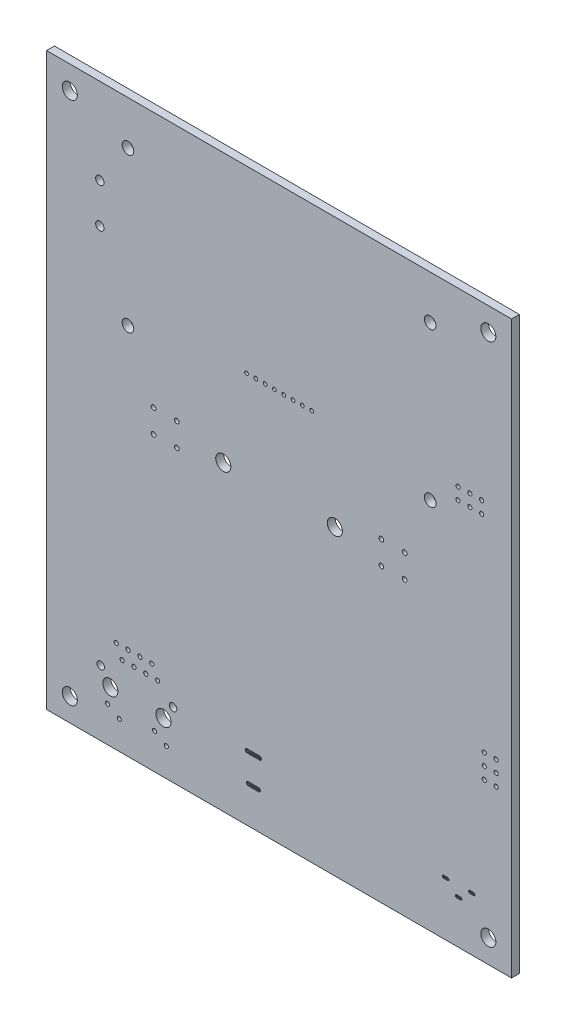
SolidWorks part; units mm, degrees
ref_plane "Front Plane" through (0, 0, 0) normal (0, 0, 1) x (1, 0, 0)
ref_plane "Top Plane" through (0, 0, 0) normal (0, 1, 0) x (1, 0, 0)
ref_plane "Right Plane" through (0, 0, 0) normal (1, 0, 0) x (0, 0, -1)
sketch "Sketch1" plane through (0, 0, 0) normal (0, 0, -1) x (-1, 0, 0)
  line L0 (7.946, 11.777) -> (8.045, 11.844)
  line L1 (8.045, 11.844) -> (8.162, 11.867)
  line L2 (8.162, 11.867) -> (8.234, 11.853)
  line L3 (8.234, 11.853) -> (8.306, 11.867)
  line L4 (8.306, 11.867) -> (8.382, 11.852)
  line L5 (8.382, 11.852) -> (8.458, 11.867)
  line L6 (8.458, 11.867) -> (8.509, 11.857)
  line L7 (8.509, 11.857) -> (8.56, 11.867)
  line L8 (8.56, 11.867) -> (8.636, 11.852)
  line L9 (8.636, 11.852) -> (8.712, 11.867)
  line L10 (8.712, 11.867) -> (8.776, 11.854)
  line L11 (8.776, 11.854) -> (8.839, 11.867)
  line L12 (8.839, 11.867) -> (8.901, 11.855)
  line L13 (8.901, 11.855) -> (8.962, 11.867)
  line L14 (8.962, 11.867) -> (9.079, 11.844)
  line L15 (9.079, 11.844) -> (9.179, 11.777)
  line L16 (9.179, 11.777) -> (9.245, 11.678)
  line L17 (9.245, 11.678) -> (9.268, 11.561)
  line L18 (9.268, 11.561) -> (9.245, 11.444)
  line L19 (9.245, 11.444) -> (9.179, 11.345)
  line L20 (9.179, 11.345) -> (9.079, 11.279)
  line L21 (9.079, 11.279) -> (8.962, 11.255)
  line L22 (8.962, 11.255) -> (8.901, 11.268)
  line L23 (8.901, 11.268) -> (8.839, 11.255)
  line L24 (8.839, 11.255) -> (8.776, 11.268)
  line L25 (8.776, 11.268) -> (8.712, 11.255)
  line L26 (8.712, 11.255) -> (8.636, 11.27)
  line L27 (8.636, 11.27) -> (8.56, 11.255)
  line L28 (8.56, 11.255) -> (8.509, 11.265)
  line L29 (8.509, 11.265) -> (8.458, 11.255)
  line L30 (8.458, 11.255) -> (8.382, 11.27)
  line L31 (8.382, 11.27) -> (8.306, 11.255)
  line L32 (8.306, 11.255) -> (8.234, 11.27)
  line L33 (8.234, 11.27) -> (8.162, 11.255)
  line L34 (8.162, 11.255) -> (8.045, 11.279)
  line L35 (8.045, 11.279) -> (7.946, 11.345)
  line L36 (7.946, 11.345) -> (7.88, 11.444)
  line L37 (7.88, 11.444) -> (7.857, 11.561)
  line L38 (7.857, 11.561) -> (7.88, 11.678)
  line L39 (7.88, 11.678) -> (7.946, 11.777)
  line L40 (13.574, 11.777) -> (13.673, 11.844)
  line L41 (13.673, 11.844) -> (13.79, 11.867)
  line L42 (13.79, 11.867) -> (13.862, 11.853)
  line L43 (13.862, 11.853) -> (13.933, 11.867)
  line L44 (13.933, 11.867) -> (14.01, 11.852)
  line L45 (14.01, 11.852) -> (14.086, 11.867)
  line L46 (14.086, 11.867) -> (14.137, 11.857)
  line L47 (14.137, 11.857) -> (14.187, 11.867)
  line L48 (14.187, 11.867) -> (14.264, 11.852)
  line L49 (14.264, 11.852) -> (14.34, 11.867)
  line L50 (14.34, 11.867) -> (14.403, 11.854)
  line L51 (14.403, 11.854) -> (14.467, 11.867)
  line L52 (14.467, 11.867) -> (14.528, 11.855)
  line L53 (14.528, 11.855) -> (14.59, 11.867)
  line L54 (14.59, 11.867) -> (14.707, 11.844)
  line L55 (14.707, 11.844) -> (14.806, 11.777)
  line L56 (14.806, 11.777) -> (14.872, 11.678)
  line L57 (14.872, 11.678) -> (14.896, 11.561)
  line L58 (14.896, 11.561) -> (14.872, 11.444)
  line L59 (14.872, 11.444) -> (14.806, 11.345)
  line L60 (14.806, 11.345) -> (14.707, 11.279)
  line L61 (14.707, 11.279) -> (14.59, 11.255)
  line L62 (14.59, 11.255) -> (14.528, 11.268)
  line L63 (14.528, 11.268) -> (14.467, 11.255)
  line L64 (14.467, 11.255) -> (14.403, 11.268)
  line L65 (14.403, 11.268) -> (14.34, 11.255)
  line L66 (14.34, 11.255) -> (14.264, 11.27)
  line L67 (14.264, 11.27) -> (14.187, 11.255)
  line L68 (14.187, 11.255) -> (14.137, 11.265)
  line L69 (14.137, 11.265) -> (14.086, 11.255)
  line L70 (14.086, 11.255) -> (14.01, 11.27)
  line L71 (14.01, 11.27) -> (13.933, 11.255)
  line L72 (13.933, 11.255) -> (13.862, 11.27)
  line L73 (13.862, 11.27) -> (13.79, 11.255)
  line L74 (13.79, 11.255) -> (13.673, 11.279)
  line L75 (13.673, 11.279) -> (13.574, 11.345)
  line L76 (13.574, 11.345) -> (13.507, 11.444)
  line L77 (13.507, 11.444) -> (13.484, 11.561)
  line L78 (13.484, 11.561) -> (13.507, 11.678)
  line L79 (13.507, 11.678) -> (13.574, 11.777)
  line L80 (11.286, 9.636) -> (11.329, 9.627)
  line L81 (11.329, 9.627) -> (11.387, 9.639)
  line L82 (11.387, 9.639) -> (11.472, 9.622)
  line L83 (11.472, 9.622) -> (11.54, 9.636)
  line L84 (11.54, 9.636) -> (11.603, 9.623)
  line L85 (11.603, 9.623) -> (11.667, 9.636)
  line L86 (11.667, 9.636) -> (11.728, 9.623)
  line L87 (11.728, 9.623) -> (11.79, 9.636)
  line L88 (11.79, 9.636) -> (11.907, 9.612)
  line L89 (11.907, 9.612) -> (12.006, 9.546)
  line L90 (12.006, 9.546) -> (12.072, 9.447)
  line L91 (12.072, 9.447) -> (12.096, 9.33)
  line L92 (12.096, 9.33) -> (12.072, 9.213)
  line L93 (12.072, 9.213) -> (12.006, 9.114)
  line L94 (12.006, 9.114) -> (11.907, 9.047)
  line L95 (11.907, 9.047) -> (11.79, 9.024)
  line L96 (11.79, 9.024) -> (11.728, 9.036)
  line L97 (11.728, 9.036) -> (11.667, 9.024)
  line L98 (11.667, 9.024) -> (11.603, 9.037)
  line L99 (11.603, 9.037) -> (11.54, 9.024)
  line L100 (11.54, 9.024) -> (11.456, 9.041)
  line L101 (11.456, 9.041) -> (11.387, 9.027)
  line L102 (11.387, 9.027) -> (11.345, 9.036)
  line L103 (11.345, 9.036) -> (11.286, 9.024)
  line L104 (11.286, 9.024) -> (11.21, 9.039)
  line L105 (11.21, 9.039) -> (11.133, 9.024)
  line L106 (11.133, 9.024) -> (11.062, 9.038)
  line L107 (11.062, 9.038) -> (10.99, 9.024)
  line L108 (10.99, 9.024) -> (10.873, 9.047)
  line L109 (10.873, 9.047) -> (10.774, 9.114)
  line L110 (10.774, 9.114) -> (10.707, 9.213)
  line L111 (10.707, 9.213) -> (10.684, 9.33)
  line L112 (10.684, 9.33) -> (10.707, 9.447)
  line L113 (10.707, 9.447) -> (10.774, 9.546)
  line L114 (10.774, 9.546) -> (10.873, 9.612)
  line L115 (10.873, 9.612) -> (10.99, 9.636)
  line L116 (10.99, 9.636) -> (11.062, 9.621)
  line L117 (11.062, 9.621) -> (11.133, 9.636)
  line L118 (11.133, 9.636) -> (11.21, 9.621)
  line L119 (11.21, 9.621) -> (11.286, 9.636)
  line L120 (55.34, 14.234) -> (55.372, 14.255)
  line L121 (55.372, 14.255) -> (55.528, 14.286)
  line L122 (55.528, 14.286) -> (55.684, 14.255)
  line L123 (55.684, 14.255) -> (55.691, 14.25)
  line L124 (55.691, 14.25) -> (55.697, 14.255)
  line L125 (55.697, 14.255) -> (55.853, 14.286)
  line L126 (55.853, 14.286) -> (56.003, 14.256)
  line L127 (56.003, 14.256) -> (56.153, 14.286)
  line L128 (56.153, 14.286) -> (56.309, 14.255)
  line L129 (56.309, 14.255) -> (56.315, 14.25)
  line L130 (56.315, 14.25) -> (56.322, 14.255)
  line L131 (56.322, 14.255) -> (56.478, 14.286)
  line L132 (56.478, 14.286) -> (56.634, 14.255)
  line L133 (56.634, 14.255) -> (56.678, 14.225)
  line L134 (56.678, 14.225) -> (56.722, 14.255)
  line L135 (56.722, 14.255) -> (56.878, 14.286)
  line L136 (56.878, 14.286) -> (57.034, 14.255)
  line L137 (57.034, 14.255) -> (57.166, 14.166)
  line L138 (57.166, 14.166) -> (57.255, 14.034)
  line L139 (57.255, 14.034) -> (57.286, 13.878)
  line L140 (57.286, 13.878) -> (57.255, 13.722)
  line L141 (57.255, 13.722) -> (57.166, 13.59)
  line L142 (57.166, 13.59) -> (57.034, 13.501)
  line L143 (57.034, 13.501) -> (56.878, 13.47)
  line L144 (56.878, 13.47) -> (56.722, 13.501)
  line L145 (56.722, 13.501) -> (56.678, 13.531)
  line L146 (56.678, 13.531) -> (56.634, 13.501)
  line L147 (56.634, 13.501) -> (56.478, 13.47)
  line L148 (56.478, 13.47) -> (56.322, 13.501)
  line L149 (56.322, 13.501) -> (56.315, 13.506)
  line L150 (56.315, 13.506) -> (56.309, 13.501)
  line L151 (56.309, 13.501) -> (56.153, 13.47)
  line L152 (56.153, 13.47) -> (56.003, 13.5)
  line L153 (56.003, 13.5) -> (55.853, 13.47)
  line L154 (55.853, 13.47) -> (55.697, 13.501)
  line L155 (55.697, 13.501) -> (55.69, 13.506)
  line L156 (55.69, 13.506) -> (55.684, 13.501)
  line L157 (55.684, 13.501) -> (55.528, 13.47)
  line L158 (55.528, 13.47) -> (55.372, 13.501)
  line L159 (55.372, 13.501) -> (55.341, 13.522)
  line L160 (55.341, 13.522) -> (55.309, 13.501)
  line L161 (55.309, 13.501) -> (55.153, 13.47)
  line L162 (55.153, 13.47) -> (54.997, 13.501)
  line L163 (54.997, 13.501) -> (54.99, 13.506)
  line L164 (54.99, 13.506) -> (54.984, 13.501)
  line L165 (54.984, 13.501) -> (54.828, 13.47)
  line L166 (54.828, 13.47) -> (54.672, 13.501)
  line L167 (54.672, 13.501) -> (54.665, 13.506)
  line L168 (54.665, 13.506) -> (54.659, 13.501)
  line L169 (54.659, 13.501) -> (54.503, 13.47)
  line L170 (54.503, 13.47) -> (54.347, 13.501)
  line L171 (54.347, 13.501) -> (54.341, 13.506)
  line L172 (54.341, 13.506) -> (54.334, 13.501)
  line L173 (54.334, 13.501) -> (54.178, 13.47)
  line L174 (54.178, 13.47) -> (54.022, 13.501)
  line L175 (54.022, 13.501) -> (53.89, 13.59)
  line L176 (53.89, 13.59) -> (53.801, 13.722)
  line L177 (53.801, 13.722) -> (53.77, 13.878)
  line L178 (53.77, 13.878) -> (53.801, 14.034)
  line L179 (53.801, 14.034) -> (53.89, 14.166)
  line L180 (53.89, 14.166) -> (54.022, 14.255)
  line L181 (54.022, 14.255) -> (54.178, 14.286)
  line L182 (54.178, 14.286) -> (54.334, 14.255)
  line L183 (54.334, 14.255) -> (54.341, 14.25)
  line L184 (54.341, 14.25) -> (54.347, 14.255)
  line L185 (54.347, 14.255) -> (54.503, 14.286)
  line L186 (54.503, 14.286) -> (54.659, 14.255)
  line L187 (54.659, 14.255) -> (54.665, 14.25)
  line L188 (54.665, 14.25) -> (54.672, 14.255)
  line L189 (54.672, 14.255) -> (54.828, 14.286)
  line L190 (54.828, 14.286) -> (54.984, 14.255)
  line L191 (54.984, 14.255) -> (54.99, 14.25)
  line L192 (54.99, 14.25) -> (54.997, 14.255)
  line L193 (54.997, 14.255) -> (55.153, 14.286)
  line L194 (55.153, 14.286) -> (55.309, 14.255)
  line L195 (55.309, 14.255) -> (55.34, 14.234)
  line L196 (54.14, 8.166) -> (54.272, 8.255)
  line L197 (54.272, 8.255) -> (54.428, 8.286)
  line L198 (54.428, 8.286) -> (54.584, 8.255)
  line L199 (54.584, 8.255) -> (54.628, 8.225)
  line L200 (54.628, 8.225) -> (54.672, 8.255)
  line L201 (54.672, 8.255) -> (54.828, 8.286)
  line L202 (54.828, 8.286) -> (54.984, 8.255)
  line L203 (54.984, 8.255) -> (55.015, 8.234)
  line L204 (55.015, 8.234) -> (55.047, 8.255)
  line L205 (55.047, 8.255) -> (55.203, 8.286)
  line L206 (55.203, 8.286) -> (55.359, 8.255)
  line L207 (55.359, 8.255) -> (55.365, 8.25)
  line L208 (55.365, 8.25) -> (55.372, 8.255)
  line L209 (55.372, 8.255) -> (55.528, 8.286)
  line L210 (55.528, 8.286) -> (55.684, 8.255)
  line L211 (55.684, 8.255) -> (55.74, 8.217)
  line L212 (55.74, 8.217) -> (55.797, 8.255)
  line L213 (55.797, 8.255) -> (55.953, 8.286)
  line L214 (55.953, 8.286) -> (56.109, 8.255)
  line L215 (56.109, 8.255) -> (56.153, 8.225)
  line L216 (56.153, 8.225) -> (56.197, 8.255)
  line L217 (56.197, 8.255) -> (56.353, 8.286)
  line L218 (56.353, 8.286) -> (56.49, 8.258)
  line L219 (56.49, 8.258) -> (56.628, 8.286)
  line L220 (56.628, 8.286) -> (56.784, 8.255)
  line L221 (56.784, 8.255) -> (56.916, 8.166)
  line L222 (56.916, 8.166) -> (57.005, 8.034)
  line L223 (57.005, 8.034) -> (57.036, 7.878)
  line L224 (57.036, 7.878) -> (57.005, 7.722)
  line L225 (57.005, 7.722) -> (56.916, 7.59)
  line L226 (56.916, 7.59) -> (56.784, 7.501)
  line L227 (56.784, 7.501) -> (56.628, 7.47)
  line L228 (56.628, 7.47) -> (56.49, 7.498)
  line L229 (56.49, 7.498) -> (56.353, 7.47)
  line L230 (56.353, 7.47) -> (56.197, 7.501)
  line L231 (56.197, 7.501) -> (56.153, 7.531)
  line L232 (56.153, 7.531) -> (56.109, 7.501)
  line L233 (56.109, 7.501) -> (55.953, 7.47)
  line L234 (55.953, 7.47) -> (55.797, 7.501)
  line L235 (55.797, 7.501) -> (55.74, 7.539)
  line L236 (55.74, 7.539) -> (55.684, 7.501)
  line L237 (55.684, 7.501) -> (55.528, 7.47)
  line L238 (55.528, 7.47) -> (55.372, 7.501)
  line L239 (55.372, 7.501) -> (55.365, 7.506)
  line L240 (55.365, 7.506) -> (55.359, 7.501)
  line L241 (55.359, 7.501) -> (55.203, 7.47)
  line L242 (55.203, 7.47) -> (55.047, 7.501)
  line L243 (55.047, 7.501) -> (55.015, 7.522)
  line L244 (55.015, 7.522) -> (54.984, 7.501)
  line L245 (54.984, 7.501) -> (54.828, 7.47)
  line L246 (54.828, 7.47) -> (54.672, 7.501)
  line L247 (54.672, 7.501) -> (54.628, 7.531)
  line L248 (54.628, 7.531) -> (54.584, 7.501)
  line L249 (54.584, 7.501) -> (54.428, 7.47)
  line L250 (54.428, 7.47) -> (54.272, 7.501)
  line L251 (54.272, 7.501) -> (54.14, 7.59)
  line L252 (54.14, 7.59) -> (54.051, 7.722)
  line L253 (54.051, 7.722) -> (54.02, 7.878)
  line L254 (54.02, 7.878) -> (54.051, 8.034)
  line L255 (54.051, 8.034) -> (54.14, 8.166)
  line L256 (0, 122.75) -> (0, 0)
  line L257 (0, 0) -> (100, 0)
  line L258 (100, 0) -> (100, 122.75)
  line L259 (100, 122.75) -> (0, 122.75)
  circle A0 centre (5, 117.75) radius 1.625
  circle A1 centre (6.4264, 85.78) radius 0.45
  circle A2 centre (6.4264, 83.24) radius 0.45
  circle A3 centre (8.9664, 85.78) radius 0.45
  circle A4 centre (11.5064, 85.78) radius 0.45
  circle A5 centre (11.5064, 83.24) radius 0.45
  circle A6 centre (3.3276, 39.0694) radius 0.45
  circle A7 centre (5.8676, 39.0694) radius 0.45
  circle A8 centre (3.3276, 36.5294) radius 0.45
  circle A9 centre (5.8676, 36.5294) radius 0.45
  circle A10 centre (8.9664, 83.24) radius 0.45
  circle A11 centre (5.8676, 33.9894) radius 0.45
  circle A12 centre (17.5, 113.35) radius 1.25
  circle A13 centre (43, 84.15) radius 0.4
  circle A14 centre (45, 84.15) radius 0.4
  circle A15 centre (49, 84.15) radius 0.4
  circle A16 centre (51, 84.15) radius 0.4
  circle A17 centre (47, 84.15) radius 0.4
  circle A18 centre (17.5, 80.25) radius 1.25
  circle A19 centre (23, 67.75) radius 0.5
  circle A20 centre (23, 62.75) radius 0.5
  circle A21 centre (28, 67.75) radius 0.5
  circle A22 centre (38, 65) radius 1.625
  circle A23 centre (28, 62.75) radius 0.5
  circle A24 centre (3.3276, 33.9894) radius 0.45
  circle A25 centre (5, 5) radius 1.625
  circle A26 centre (55, 84.15) radius 0.4
  circle A27 centre (57, 84.15) radius 0.4
  circle A28 centre (53, 84.15) radius 0.4
  circle A29 centre (72, 67.75) radius 0.5
  circle A30 centre (77, 67.75) radius 0.5
  circle A31 centre (62, 65) radius 1.625
  circle A32 centre (72, 62.75) radius 0.5
  circle A33 centre (77, 62.75) radius 0.5
  circle A34 centre (77.393, 19.88) radius 0.45
  circle A35 centre (76.123, 17.34) radius 0.45
  circle A36 centre (82.5, 80.25) radius 1.25
  circle A37 centre (82.5, 113.35) radius 1.25
  circle A38 centre (79.943, 19.88) radius 0.45
  circle A39 centre (88.55, 104.3) radius 0.9
  circle A40 centre (95, 117.75) radius 1.625
  circle A41 centre (88.55, 95.8) radius 0.9
  circle A42 centre (81.213, 17.34) radius 0.45
  circle A43 centre (82.483, 19.88) radius 0.45
  circle A44 centre (78.663, 17.34) radius 0.45
  circle A45 centre (85.023, 19.88) radius 0.45
  circle A46 centre (83.753, 17.34) radius 0.45
  circle A47 centre (72.798, 14.05) radius 0.8
  circle A48 centre (86.288, 11) radius 1.625
  circle A49 centre (88.348, 14.05) radius 0.8
  circle A50 centre (74.858, 11) radius 1.625
  circle A51 centre (74.248, 6.1) radius 0.445
  circle A52 centre (76.788, 7.62) radius 0.445
  circle A53 centre (84.358, 6.1) radius 0.445
  circle A54 centre (86.898, 7.62) radius 0.445
  circle A55 centre (95, 5) radius 1.625
extrude "Boss-Extrude1" add sketch "Sketch1" against normal blind 1.6916
